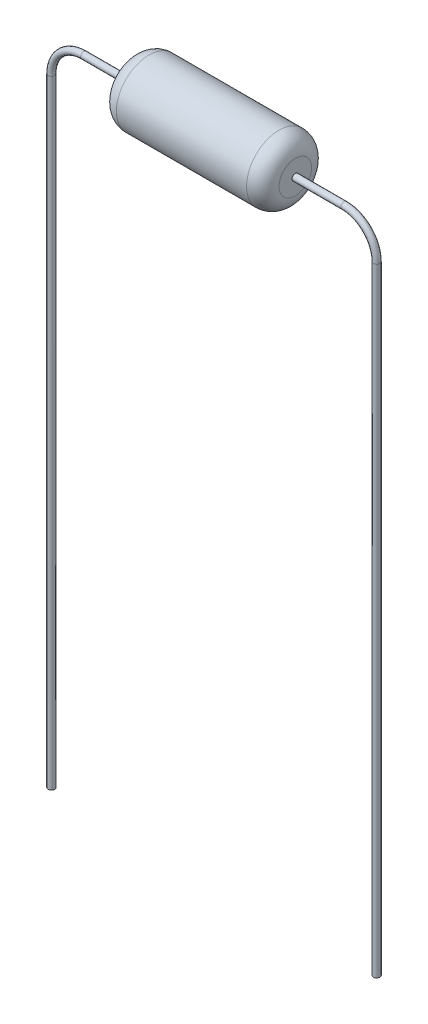
SolidWorks part; units mm, degrees
ref_plane "Front Plane" through (0, 0, 0) normal (0, 0, 1) x (1, 0, 0)
ref_plane "Top Plane" through (0, 0, 0) normal (0, 1, 0) x (1, 0, 0)
ref_plane "Right Plane" through (0, 0, 0) normal (1, 0, 0) x (0, 0, -1)
sketch "Sketch1" plane through (0, 0, 0) normal (0, 0, 1) x (1, 0, 0)
  line L0 (15.8506, 0) -> (-17.524, 0) construction
  line L1 (2.5, 0) -> (2.5, 0.5)
  line L2 (2, 1) -> (-2, 1)
  line L3 (-2.5, 0.5) -> (-2.5, 0)
  line L4 (2.5, 0) -> (-2.5, 0)
  arc A0 (2, 1) -> (2.5, 0.5) centre (2, 0.5) cw
  arc A1 (-2.5, 0.5) -> (-2, 1) centre (-2, 0.5) cw
  point P11 (0, 0)
  point P12 (-94.4312, 0)
  point P13 (0, 0)
  point P14 (-17.524, 0)
  point P15 (15.8506, 0)
  dimension "D1" = 0.5
  dimension "D2" = 0.5
  dimension "D3" = 0.5
  dimension "D4" = 2.5
  dimension "D5" = 2.5
revolve "Revolve1" add sketch "Sketch1" angle 360 about L0
sketch "Sketch2" plane through (0, 0, 0) normal (0, 0, 1) x (1, 0, 0)
  line L0 (2.5, 0) -> (4, 0)
  line L1 (2.5, -0.5) -> (2.5, 0.5) construction
  line L2 (5, -1) -> (5, -20)
  arc A0 (5, -1) -> (4, 0) centre (4, -1) ccw
  point P8 (5, 0)
  point P9 (0, 0)
  dimension "D3" = 1
  dimension "D1" = 2.5
  dimension "D2" = 20
sketch "Sketch3" plane through (2.5, 0, 0) normal (1, 0, 0) x (0, 0, -1)
  circle A0 centre (0, 0) radius 0.1
  dimension "D1" = 0.2
sweep "Sweep1" add profiles "Sketch3" path "Sketch2"
mirror "Mirror1" about plane through (0, 0, 0) normal (1, 0, 0) of "Sweep1"
